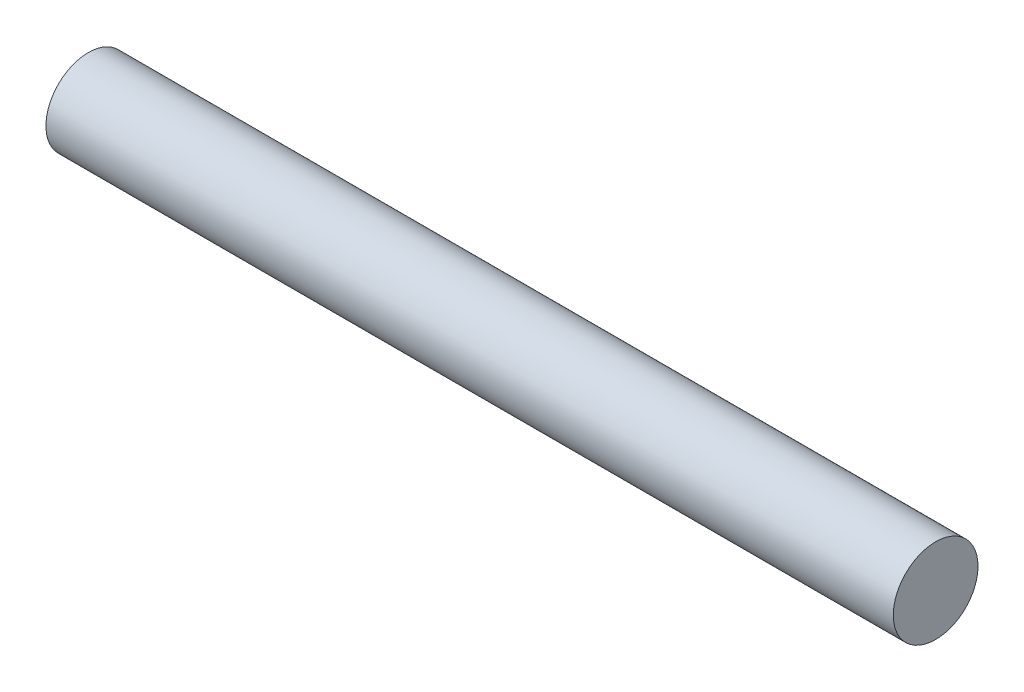
SolidWorks part; units mm, degrees
material "ABS"
ref_plane "前视基准面" through (0, 0, 0) normal (0, 0, 1) x (1, 0, 0)
ref_plane "上视基准面" through (0, 0, 0) normal (0, 1, 0) x (1, 0, 0)
ref_plane "右视基准面" through (0, 0, 0) normal (1, 0, 0) x (0, 0, -1)
other "Configuration Table"
sketch "草图1" plane through (0, 0, 0) normal (1, 0, 0) x (0, 0, -1)
  circle A0 centre (0, 0) radius 25
  dimension "D1" = 50
extrude "凸台-拉伸1" add sketch "草图1" along normal blind 500
